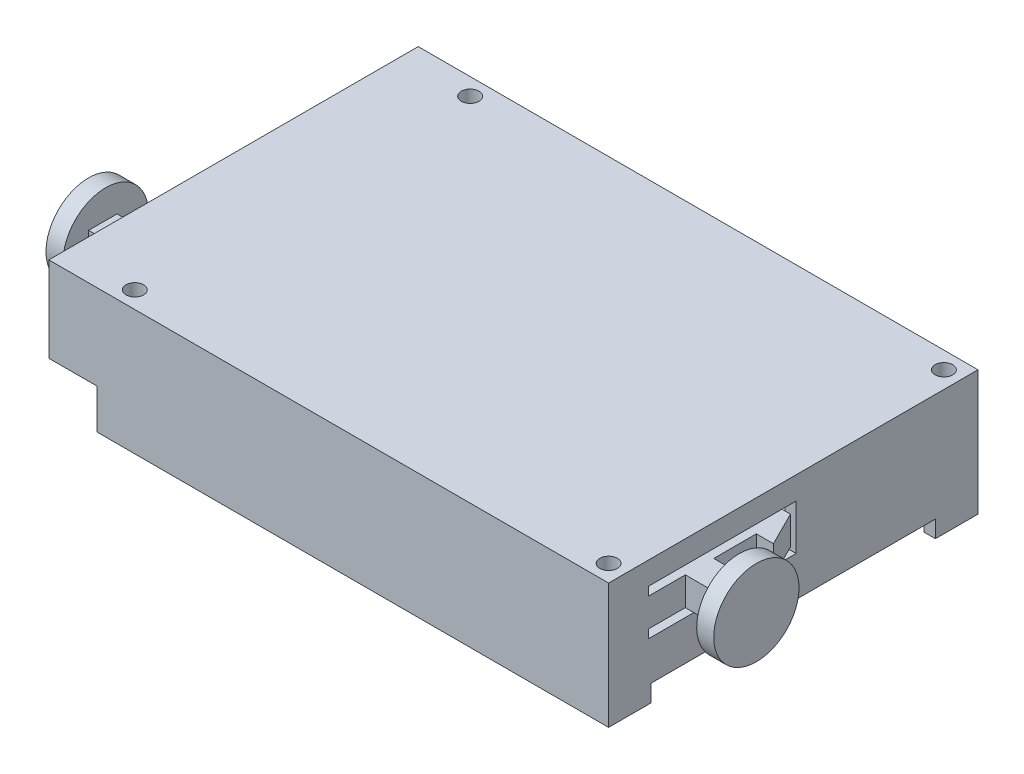
SolidWorks part; units mm, degrees
ref_plane "前视基准面" through (0, 0, 0) normal (0, 0, 1) x (1, 0, 0)
ref_plane "上视基准面" through (0, 0, 0) normal (0, 1, 0) x (1, 0, 0)
ref_plane "右视基准面" through (0, 0, 0) normal (1, 0, 0) x (0, 0, -1)
sketch "草图1" plane through (0, 0, 0) normal (0, 1, 0) x (1, 0, 0)
  line L1 (-49.25, 32.5) -> (49.25, 32.5)
  line L2 (-49.25, 32.5) -> (-49.25, -32.5)
  line L3 (-49.25, -32.5) -> (49.25, -32.5)
  line L4 (49.25, 32.5) -> (49.25, -32.5)
  line L5 (-49.25, 32.5) -> (49.25, -32.5) construction
  line L6 (-49.25, -32.5) -> (49.25, 32.5) construction
  point P0 (0, 0)
  dimension "D1" = 98.5
  dimension "D2" = 65
extrude "凸台-拉伸1" add sketch "草图1" along normal blind 2
ref_plane "基准面1" through (0, 0, 0) normal (0, -1, 0) x (-1, 0, 0)
sketch "草图2" plane through (0, 0, 0) normal (0, -1, 0) x (-1, 0, 0)
  line L0 (49.25, 32.5) -> (49.25, -32.5) construction
  line L1 (-47.25, 31) -> (47.25, 31)
  line L2 (-47.25, 31) -> (-47.25, -31)
  line L3 (-47.25, -31) -> (47.25, -31)
  line L4 (47.25, 31) -> (47.25, -31)
  line L5 (-47.25, 31) -> (47.25, -31) construction
  line L6 (-47.25, -31) -> (47.25, 31) construction
  line L7 (49.25, -32.5) -> (-49.25, -32.5) construction
  line L9 (-49.25, 32.5) -> (49.25, 32.5)
  line L10 (-49.25, 32.5) -> (-49.25, -32.5)
  line L11 (-49.25, -32.5) -> (49.25, -32.5)
  line L12 (49.25, 32.5) -> (49.25, -32.5)
  point P0 (0, 0)
  dimension "D1" = 2
  dimension "D2" = 1.5
extrude "凸台-拉伸2" add sketch "草图2" along normal blind 20
ref_plane "基准面2" through (-49.25, 0, 0) normal (-1, 0, 0) x (0, 0, 1)
sketch "草图3" plane through (-49.25, 0, 0) normal (-1, 0, 0) x (0, 0, 1)
  line L0 (32.5, -20) -> (-32.5, -20) construction
  line L1 (-20.4, -20) -> (-0.4, -20)
  line L2 (-20.4, -20) -> (-20.4, -14)
  line L3 (-20.4, -14) -> (-0.4, -14)
  line L4 (-0.4, -20) -> (-0.4, -14)
  line L5 (-32.5, 2) -> (-32.5, -20) construction
  line L7 (32.5, -20) -> (16.6, -20)
  line L8 (32.5, -20) -> (32.5, -13)
  line L9 (32.5, -13) -> (16.6, -13)
  line L10 (16.6, -20) -> (16.6, -13)
  dimension "D1" = 12.1
  dimension "D2" = 20
  dimension "D3" = 6
  dimension "D4" = 17
  dimension "D5" = 7
extrude "切除-拉伸1" cut sketch "草图3" against normal blind 8.5
ref_plane "基准面3" through (0, 2, 0) normal (0, 1, 0) x (1, 0, 0)
ref_plane "基准面4" through (0, -20, 0) normal (0, -1, 0) x (-1, 0, 0)
sketch "草图7" plane through (-49.25, 0, 0) normal (-1, 0, 0) x (0, 0, 1)
  line L0 (32.5, 2) -> (32.5, -13) construction
  line L1 (25.5, -2) -> (-0.5, -2)
  line L2 (25.5, -2) -> (25.5, -10)
  line L3 (25.5, -10) -> (-0.5, -10)
  line L4 (-0.5, -2) -> (-0.5, -10)
  line L5 (-32.5, 2) -> (32.5, 2) construction
  line L7 (25.5, -3.5) -> (0.5, -3.5)
  line L8 (25.5, -3.5) -> (25.5, -8.5)
  line L9 (25.5, -8.5) -> (0.5, -8.5)
  line L10 (0.5, -3.5) -> (0.5, -8.5)
  dimension "D1" = 8
  dimension "D2" = 7
  dimension "D3" = 26
  dimension "D4" = 4
  dimension "D5" = 1.5
  dimension "D6" = 25
  dimension "D7" = 1.5
extrude "切除-拉伸5" cut sketch "草图7" against normal through all contours L10 L7 L2 L1 L4 L3 L9
ref_plane "基准面5" through (0, -3.5, 0) normal (0, 1, 0) x (1, 0, 0)
sketch "草图8" plane through (0, -3.5, 0) normal (0, 1, 0) x (1, 0, 0)
  line L0 (-49.25, -0.5) -> (-52.25, -6.5)
  line L1 (-52.25, -6.5) -> (-49.25, -6.5)
  line L2 (-49.25, -25.5) -> (-49.25, -0.5) construction
  line L3 (-49.25, -0.5) -> (-49.25, -6.5)
  line L4 (49.25, -0.5) -> (52.25, -6.5)
  line L5 (52.25, -6.5) -> (49.25, -6.5)
  line L6 (49.25, -25.5) -> (49.25, -0.5) construction
  line L7 (49.25, -6.5) -> (49.25, -0.5)
  line L9 (49.25, -14) -> (55.75, -14)
  line L10 (49.25, -14) -> (49.25, -19)
  line L11 (49.25, -19) -> (55.75, -19)
  line L12 (55.75, -14) -> (55.75, -19)
  line L13 (-49.25, -14) -> (-55.75, -14)
  line L14 (-49.25, -14) -> (-49.25, -19)
  line L15 (-49.25, -19) -> (-55.75, -19)
  line L16 (-55.75, -14) -> (-55.75, -19)
  dimension "D1" = 3
  dimension "D2" = 6
  dimension "D3" = 3
  dimension "D4" = 6
  dimension "D5" = 6.5
  dimension "D6" = 5
  dimension "D7" = 7.5
  dimension "D8" = 6.5
  dimension "D9" = 5
  dimension "D10" = 7.5
extrude "凸台-拉伸5" add sketch "草图8" against normal blind 5
sketch "草图9" plane through (0, 2, 0) normal (0, 1, 0) x (1, 0, 0)
  line L0 (49.25, -32.5) -> (49.25, 32.5) construction
  line L1 (49.25, 32.5) -> (-49.25, 32.5) construction
  line L2 (-49.25, -32.5) -> (49.25, -32.5) construction
  circle A0 centre (46.25, 29.5) radius 1.55
  circle A1 centre (46.25, -29.5) radius 1.55
  circle A2 centre (-37.117, 29.5) radius 1.55
  circle A3 centre (-37.117, -29.5) radius 1.55
  dimension "D1" = 3.1
  dimension "3.1" = 3.1
  dimension "D5" = 3
  dimension "D8" = 3.1
  dimension "D9" = 3.1
  dimension "D2" = 3
  dimension "D3" = 3
  dimension "D6" = 3
  dimension "D7" = 83.367
extrude "切除-拉伸7" cut sketch "草图9" against normal through all
ref_plane "基准面6" through (0, 0, 0) normal (0, -1, 0) x (-1, 0, 0)
sketch "草图10" plane through (0, 0, 0) normal (0, -1, 0) x (-1, 0, 0)
  circle A0 centre (-46.25, 29.5) radius 1.55
  circle A1 centre (-46.25, 29.5) radius 2.25
  circle A2 centre (37.117, 29.5) radius 1.55
  circle A3 centre (37.117, 29.5) radius 2.25
  circle A4 centre (-46.25, -29.5) radius 1.55
  circle A5 centre (-46.25, -29.5) radius 2.25
  circle A6 centre (37.117, -29.5) radius 1.55
  circle A7 centre (37.117, -29.5) radius 2.25
  arc A8 (37.5075, -31) -> (36.7265, -31) centre (37.117, -29.5) ccw construction
  dimension "D1" = 4.5
  dimension "D2" = 4.5
  dimension "D3" = 3.1
  dimension "D4" = 3.1
  dimension "D5" = 4.5
  dimension "D6" = 3.1
  dimension "D7" = 4.5
extrude "凸台-拉伸6" add sketch "草图10" along normal through all
ref_plane "基准面7" through (49.25, 0, 0) normal (1, 0, 0) x (0, 0, -1)
sketch "草图11" plane through (49.25, 0, 0) normal (1, 0, 0) x (0, 0, -1)
  line L0 (32.5, -20) -> (-32.5, -20) construction
  line L1 (-25, -17) -> (25, -17)
  line L2 (-25, -17) -> (-25, -23)
  line L3 (-25, -23) -> (25, -23)
  line L4 (25, -17) -> (25, -23)
  line L5 (-25, -17) -> (25, -23) construction
  line L6 (-25, -23) -> (25, -17) construction
  point P0 (0, -20)
  dimension "D1" = 6
  dimension "5" = 50
extrude "切除-拉伸8" cut sketch "草图11" against normal blind 10
sketch "草图15" plane through (0, 0, 0) normal (0, -1, 0) x (-1, 0, 0)
  line L0 (35.4399, 31) -> (-44.5729, 31) construction
  line L1 (-43.95, 31) -> (-47.25, 31)
  line L2 (-43.95, 31) -> (-43.95, 26)
  line L3 (-43.95, 26) -> (-47.25, 26)
  line L4 (-47.25, 31) -> (-47.25, 26)
  line L5 (-47.25, 27.4844) -> (-47.25, 25) construction
  line L6 (-44.5729, -31) -> (35.4399, -31) construction
  line L7 (-43.95, -31) -> (-47.25, -31)
  line L8 (-43.95, -31) -> (-43.95, -26)
  line L9 (-43.95, -26) -> (-47.25, -26)
  line L10 (-47.25, -31) -> (-47.25, -26)
  line L11 (-47.25, -25) -> (-47.25, -27.4844) construction
  line L12 (35.4399, 31) -> (-44.5729, 31) construction
  line L13 (34.817, 31) -> (41.817, 31)
  line L14 (34.817, 31) -> (34.817, 26)
  line L15 (34.817, 26) -> (41.817, 26)
  line L16 (41.817, 31) -> (41.817, 26)
  line L17 (40.75, -31) -> (40.75, -32.5) construction
  line L18 (34.817, -31) -> (40.75, -31)
  line L19 (34.817, -31) -> (34.817, -26)
  line L20 (34.817, -26) -> (40.75, -26)
  line L21 (40.75, -31) -> (40.75, -26)
  circle A0 centre (-46.25, 29.5) radius 2.25
  arc A1 (-47.25, 27.4844) -> (-44.5729, 31) centre (-46.25, 29.5) ccw construction
  circle A2 centre (-46.25, -29.5) radius 2.25
  arc A3 (35.4399, 31) -> (38.7941, 31) centre (37.117, 29.5) ccw construction
  circle A4 centre (37.117, -29.5) radius 1.55 construction
  circle A5 centre (37.117, -29.5) radius 2.25
  circle A6 centre (37.117, 29.5) radius 2.25
  dimension "D5" = 2.3
  dimension "D6" = 5
  dimension "D1" = 3.3
  dimension "D2" = 5
  dimension "D3" = 3.3
  dimension "D4" = 5
  dimension "D7" = 7
  dimension "D8" = 5
  dimension "D9" = 2.3
extrude "凸台-拉伸8" add sketch "草图15" along normal through all contours A5 L18 L21 L20 L19 | A2 L7 L8 L9 L10 | A0 L4 L3 L2 L1 | A6 L13 L14 L15 L16
ref_plane "基准面8" through (0, -20, 0) normal (0, -1, 0) x (-1, 0, 0)
sketch "草图16" plane through (0, -20, 0) normal (0, -1, 0) x (-1, 0, 0)
  circle A0 centre (-46.25, 29.5) radius 1.75
  circle A1 centre (37.117, 29.5) radius 1.75
  circle A2 centre (37.117, -29.5) radius 1.75
  circle A3 centre (-46.25, -29.5) radius 1.75
  dimension "D1" = 3.5
  dimension "D2" = 3.5
  dimension "D3" = 3.5
  dimension "D4" = 3.5
extrude "切除-拉伸9" cut sketch "草图16" against normal blind 15
ref_plane "基准面9" through (55.75, 0, 0) normal (1, 0, 0) x (0, 0, -1)
sketch "草图17" plane through (55.75, 0, 0) normal (1, 0, 0) x (0, 0, -1)
  circle A0 centre (-16, -6) radius 7.5
  dimension "D1" = 15
extrude "凸台-拉伸9" add sketch "草图17" along normal blind 3
ref_plane "基准面10" through (-55.75, 0, 0) normal (-1, 0, 0) x (0, 0, 1)
sketch "草图18" plane through (-55.75, 0, 0) normal (-1, 0, 0) x (0, 0, 1)
  circle A0 centre (16, -6) radius 7.5
  dimension "D1" = 15
extrude "凸台-拉伸10" add sketch "草图18" along normal blind 3
